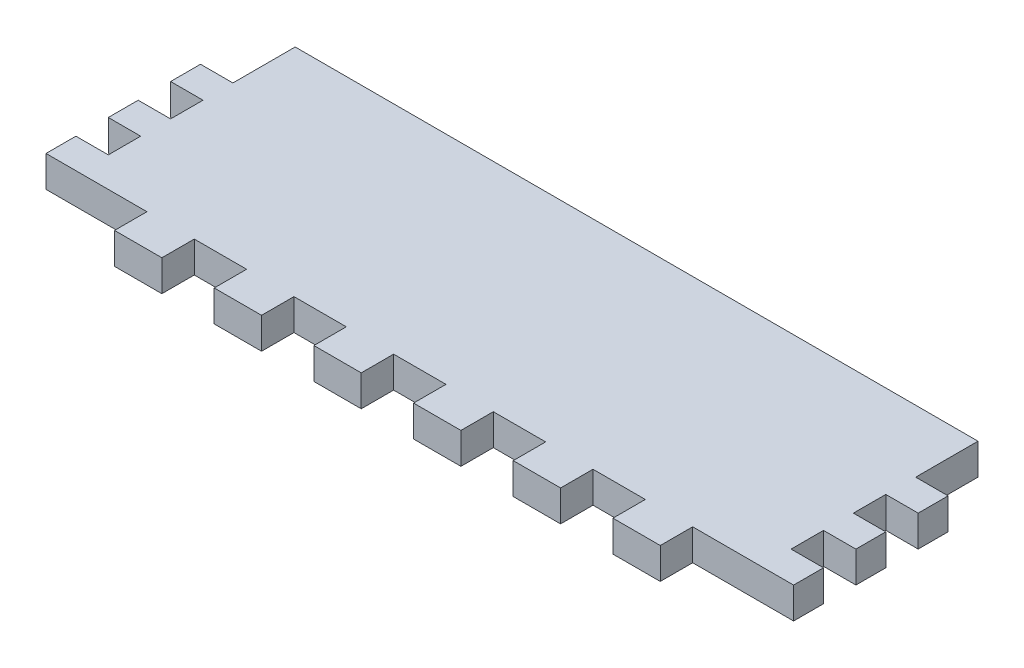
SolidWorks part; units mm, degrees
ref_plane "Front Plane" through (0, 0, 0) normal (0, 0, 1) x (1, 0, 0)
ref_plane "Top Plane" through (0, 0, 0) normal (0, 1, 0) x (1, 0, 0)
ref_plane "Right Plane" through (0, 0, 0) normal (1, 0, 0) x (0, 0, -1)
sketch "Sketch1" plane through (0, 0, 0) normal (0, 1, 0) x (1, 0, 0)
  line L1 (-38.1, -12.7) -> (38.1, -12.7)
  line L2 (-38.1, -12.7) -> (-38.1, 12.7)
  line L3 (-38.1, 12.7) -> (38.1, 12.7)
  line L4 (38.1, -12.7) -> (38.1, 12.7)
  line L5 (-38.1, -12.7) -> (38.1, 12.7) construction
  line L6 (-38.1, 12.7) -> (38.1, -12.7) construction
  point P0 (0, 0)
  dimension "D1" = 76.2
  dimension "D2" = 25.4
extrude "Boss-Extrude1" add sketch "Sketch1" along normal blind 3.175
sketch "Sketch2" plane through (0, 0, 0) normal (0, -1, 0) x (1, 0, 0)
  circle A0 centre (0, 0) radius 6.8807
sketch "Sketch3" plane through (0, 3.175, 0) normal (0, 1, 0) x (1, 0, 0)
  line L0 (-38.1, -12.7) -> (38.1, -12.7) construction
  line L1 (38.1, -9.398) -> (27.813, -9.398)
  line L2 (38.1, -9.398) -> (38.1, -12.7)
  line L3 (38.1, -12.7) -> (27.813, -12.7)
  line L4 (27.813, -9.398) -> (27.813, -12.7)
  line L5 (22.987, -12.7) -> (17.653, -12.7)
  line L6 (22.987, -12.7) -> (22.987, -9.398)
  line L7 (22.987, -9.398) -> (17.653, -9.398)
  line L8 (17.653, -12.7) -> (17.653, -9.398)
  line L9 (12.827, -12.7) -> (7.493, -12.7)
  line L10 (12.827, -12.7) -> (12.827, -9.398)
  line L11 (12.827, -9.398) -> (7.493, -9.398)
  line L12 (7.493, -12.7) -> (7.493, -9.398)
  line L13 (2.667, -12.7) -> (-2.667, -12.7)
  line L14 (2.667, -12.7) -> (2.667, -9.398)
  line L15 (2.667, -9.398) -> (-2.667, -9.398)
  line L16 (-2.667, -12.7) -> (-2.667, -9.398)
  line L17 (-7.493, -12.7) -> (-12.827, -12.7)
  line L18 (-7.493, -12.7) -> (-7.493, -9.398)
  line L19 (-7.493, -9.398) -> (-12.827, -9.398)
  line L20 (-12.827, -12.7) -> (-12.827, -9.398)
  line L21 (-17.653, -12.7) -> (-22.987, -12.7)
  line L22 (-17.653, -12.7) -> (-17.653, -9.398)
  line L23 (-17.653, -9.398) -> (-22.987, -9.398)
  line L24 (-22.987, -12.7) -> (-22.987, -9.398)
  line L25 (0, 0) -> (0, -4.1419) construction
  line L26 (-27.813, -9.398) -> (-27.813, -12.7)
  line L27 (-38.1, -12.7) -> (-27.813, -12.7)
  line L28 (-38.1, -9.398) -> (-38.1, -12.7)
  line L29 (-38.1, -9.398) -> (-27.813, -9.398)
  line L39 (38.1, -12.7) -> (38.1, 12.7) construction
  line L40 (38.1, -6.35) -> (34.798, -6.35)
  line L41 (38.1, -6.35) -> (38.1, -3.048)
  line L42 (38.1, -3.048) -> (34.798, -3.048)
  line L43 (34.798, -6.35) -> (34.798, -3.048)
  line L48 (38.1, 0) -> (34.798, 0)
  line L49 (38.1, 0) -> (38.1, 3.302)
  line L50 (38.1, 3.302) -> (34.798, 3.302)
  line L51 (34.798, 0) -> (34.798, 3.302)
  line L52 (38.1, 6.35) -> (34.798, 6.35)
  line L53 (38.1, 6.35) -> (38.1, 9.652)
  line L55 (34.798, 6.35) -> (34.798, 9.652)
  line L57 (38.1, 9.652) -> (34.798, 9.652) [skipped]
  line L58 (38.1, 9.652) -> (38.1, 12.7)
  line L59 (38.1, 12.7) -> (34.798, 12.7)
  line L60 (38.1, 12.7) -> (-38.1, 12.7) construction
  line L61 (34.798, 12.7) -> (34.798, 9.652)
  line L62 (-34.798, 12.7) -> (-34.798, 9.652)
  line L63 (-38.1, 12.7) -> (-34.798, 12.7)
  line L64 (-38.1, 9.652) -> (-38.1, 12.7)
  line L65 (-34.798, 6.35) -> (-34.798, 9.652)
  line L66 (-38.1, 6.35) -> (-38.1, 9.652)
  line L67 (-38.1, 6.35) -> (-34.798, 6.35)
  line L68 (-34.798, 0) -> (-34.798, 3.302)
  line L69 (-38.1, 3.302) -> (-34.798, 3.302)
  line L70 (-38.1, 0) -> (-38.1, 3.302)
  line L71 (-38.1, 0) -> (-34.798, 0)
  line L72 (-34.798, -6.35) -> (-34.798, -3.048)
  line L73 (-38.1, -3.048) -> (-34.798, -3.048)
  line L74 (-38.1, -6.35) -> (-38.1, -3.048)
  line L75 (-38.1, -6.35) -> (-34.798, -6.35)
  point P12 (20.32, -12.7)
  dimension "D1" = 3.302
  dimension "D2" = 3.302
  dimension "D3" = 5.334
  dimension "D4" = 17.78
  dimension "D5" = 3.302
  dimension "D6" = 6.35
  dimension "D7" = 3
extrude "Cut-Extrude1" cut sketch "Sketch3" against normal through all
